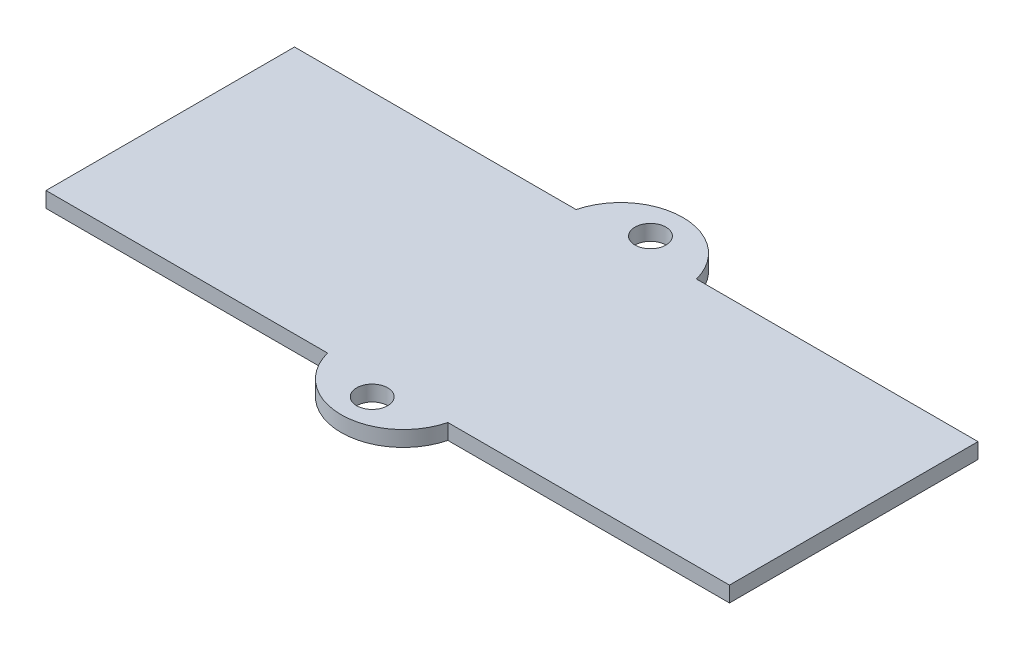
SolidWorks part; units mm, degrees
ref_plane "Front Plane" through (0, 0, 0) normal (0, 0, 1) x (1, 0, 0)
ref_plane "Top Plane" through (0, 0, 0) normal (0, 1, 0) x (1, 0, 0)
ref_plane "Right Plane" through (0, 0, 0) normal (1, 0, 0) x (0, 0, -1)
sketch "Sketch1" plane through (0.8789, -232.2037, 17.8384) normal (0, 1, 0) x (1, 0, 0)
  line L0 (-76.6054, -50.0886) -> (-76.6054, -18.0886) construction
  line L1 (-40.3514, -50.0886) -> (-76.6054, -50.0886) construction
  line L2 (-76.6054, -18.0886) -> (-40.3514, -18.0886) construction
  line L3 (-24.8595, -18.0886) -> (11.3946, -18.0886) construction
  line L4 (11.3946, -18.0886) -> (11.3946, -50.0886) construction
  line L5 (11.3946, -50.0886) -> (-24.8595, -50.0886) construction
  line L6 (-76.6054, -50.0886) -> (-76.6054, -18.0886)
  line L7 (-40.3514, -50.0886) -> (-76.6054, -50.0886)
  line L8 (-76.6054, -18.0886) -> (-40.3514, -18.0886)
  line L9 (-24.8595, -18.0886) -> (11.3946, -18.0886)
  line L10 (11.3946, -18.0886) -> (11.3946, -50.0886)
  line L11 (11.3946, -50.0886) -> (-24.8595, -50.0886)
  arc A0 (-24.8595, -18.0886) -> (-40.3514, -18.0886) centre (-32.6054, -20.0886) ccw construction
  arc A1 (-40.3514, -50.0886) -> (-24.8595, -50.0886) centre (-32.6054, -48.0886) ccw construction
  arc A2 (-24.8595, -18.0886) -> (-40.3514, -18.0886) centre (-32.6054, -20.0886) ccw
  arc A3 (-40.3514, -50.0886) -> (-24.8595, -50.0886) centre (-32.6054, -48.0886) ccw
  circle A4 centre (-32.6054, -52.0886) radius 2
  circle A5 centre (-32.6054, -16.2592) radius 2
  dimension "D1" = 4
  dimension "D2" = 4
extrude "Boss-Extrude1" add sketch "Sketch1" along normal blind 2
